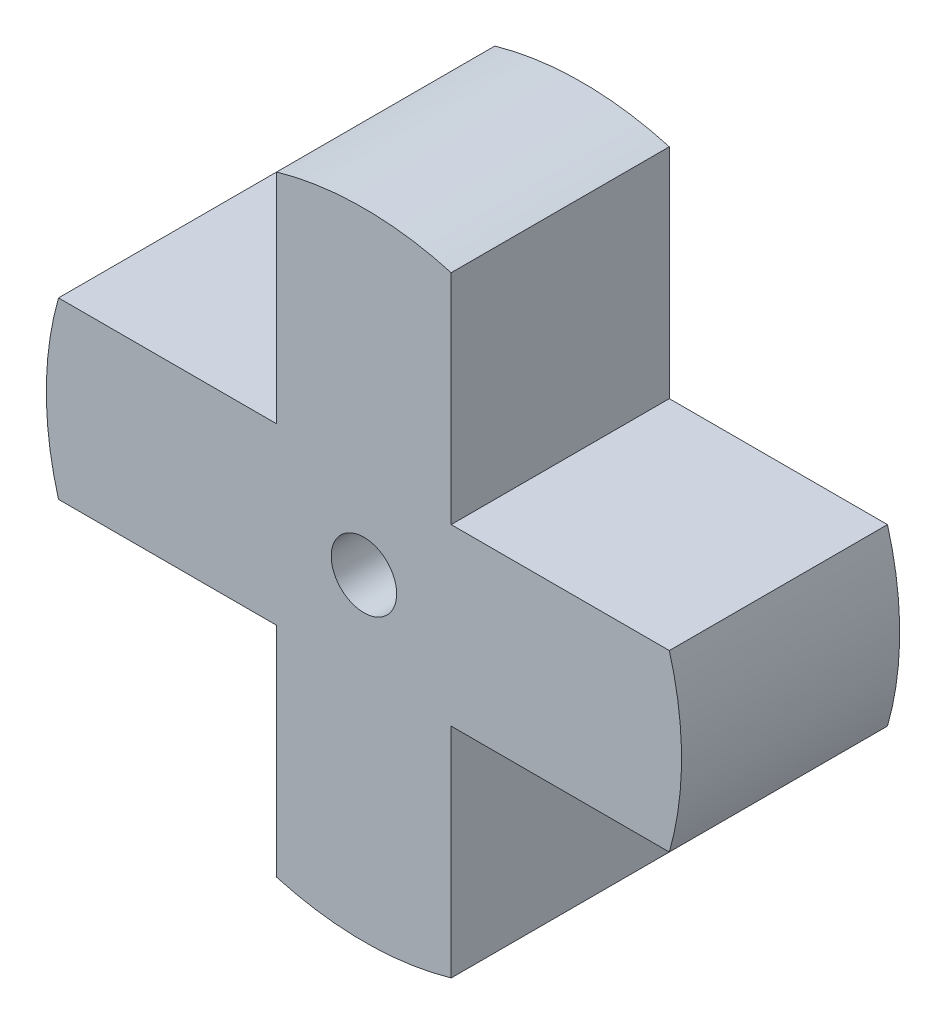
SolidWorks part; units mm, degrees
ref_plane "Front Plane" through (0, 0, 0) normal (0, 0, 1) x (1, 0, 0)
ref_plane "Top Plane" through (0, 0, 0) normal (0, 1, 0) x (1, 0, 0)
ref_plane "Right Plane" through (0, 0, 0) normal (1, 0, 0) x (0, 0, -1)
sketch "Sketch1" plane through (0, 0, 0) normal (0, 0, 1) x (1, 0, 0)
  line L0 (0, 0) -> (7, 0) construction
  line L1 (-7, 0) -> (0, 0) construction
  line L2 (0, 7) -> (0, 0) construction
  line L3 (0, -7) -> (0, 0) construction
  line L4 (0, -2) -> (7, -2)
  line L5 (-2, 7) -> (-2, 0)
  line L6 (-7, -2) -> (0, -2)
  line L7 (2, -7) -> (2, 0)
  line L8 (0, 2) -> (7, 2)
  line L9 (2, 7) -> (2, 0)
  line L10 (-7, 2) -> (0, 2)
  line L11 (-2, -7) -> (-2, 0)
  circle A0 centre (0, 0) radius 7 construction
  circle A1 centre (0, 0) radius 0.75
  circle A2 centre (0, 0) radius 7.2801
  dimension "D1" = 1.5
  dimension "D2" = 14
  dimension "D3" = 2
  dimension "D4" = 2
extrude "Boss-Extrude1" add sketch "Sketch1" along normal blind 5 contours L10 A2 L6 L11 L5 | L9 A2 L5 L10 L8 | L11 L6 L4 L7 L9 L8 L10 L5 A1 | L11 A2 L7 L4 L6 | L4 A2 L8 L9 L7
